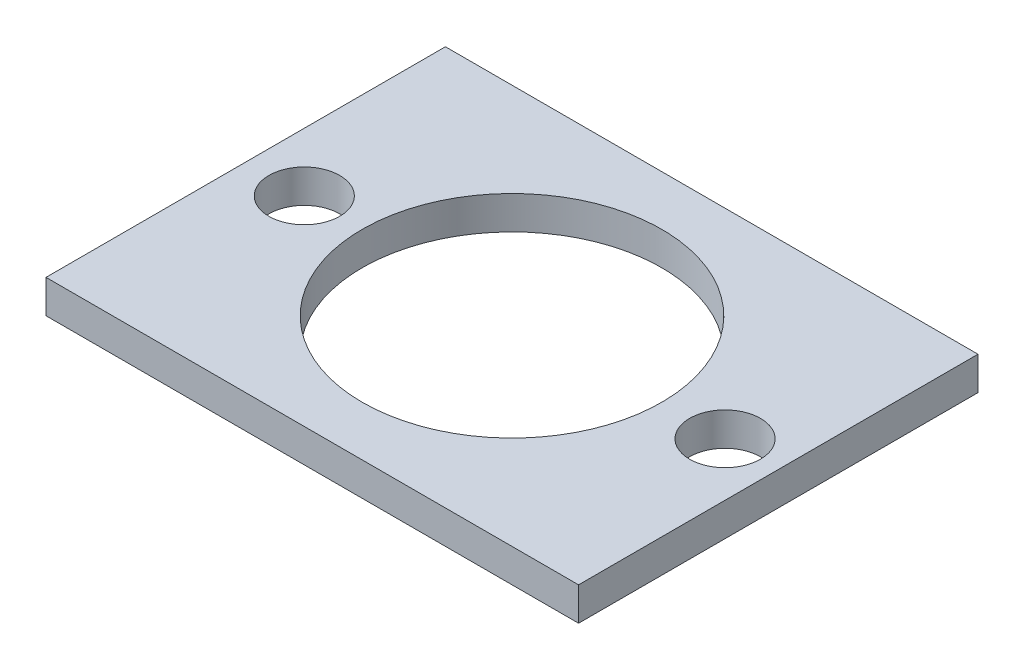
SolidWorks part; units mm, degrees
ref_plane "Front Plane" through (0, 0, 0) normal (0, 0, 1) x (1, 0, 0)
ref_plane "Top Plane" through (0, 0, 0) normal (0, 1, 0) x (1, 0, 0)
ref_plane "Right Plane" through (0, 0, 0) normal (1, 0, 0) x (0, 0, -1)
sketch "Sketch1" plane through (0, 0, 0) normal (0, 1, 0) x (1, 0, 0)
  line L1 (25.4, -19.05) -> (-25.4, -19.05)
  line L2 (25.4, -19.05) -> (25.4, 19.05)
  line L3 (25.4, 19.05) -> (-25.4, 19.05)
  line L4 (-25.4, -19.05) -> (-25.4, 19.05)
  line L5 (25.4, -19.05) -> (-25.4, 19.05) construction
  line L6 (25.4, 19.05) -> (-25.4, -19.05) construction
  circle A0 centre (0, 0) radius 14.2875
  dimension "D1" = 28.575
  dimension "D2" = 50.8
  dimension "D3" = 19.05
extrude "Boss-Extrude1" add sketch "Sketch1" along normal blind 3.175
hole_wizard "1/4 Clearance Hole1" positions "Sketch2" profile "Sketch3" hole size "1/4" standard "ANSI Inch" end condition through all
sketch "Sketch2" plane through (0, 3.175, 0) normal (0, 1, 0) x (1, 0, 0)
  line L0 (-25.4, 0) -> (25.4, 0) construction
  line L1 (-25.4, 19.05) -> (-25.4, -19.05) construction
  line L2 (25.4, -19.05) -> (25.4, 19.05) construction
  point P8 (-19.812, 0)
  point P10 (20.32, 0)
  dimension "D1" = 5.588
  dimension "D2" = 5.08
sketch "Sketch3" plane through (20.32, 3.175, 0) normal (1, 0, 0) x (0, 0, 1)
  line L0 (0, 0) -> (0, 3.175)
  line L1 (0, 3.175) -> (3.3782, 3.175)
  line L2 (3.3782, 3.175) -> (3.3782, 0)
  line L5 (3.3782, 0) -> (0, 0)
  line L11 (0, -6.35) -> (0, 107.95) construction
  dimension "Thru Hole Dia." = 6.7564
  dimension "Thru Hole Depth" = 3.175
